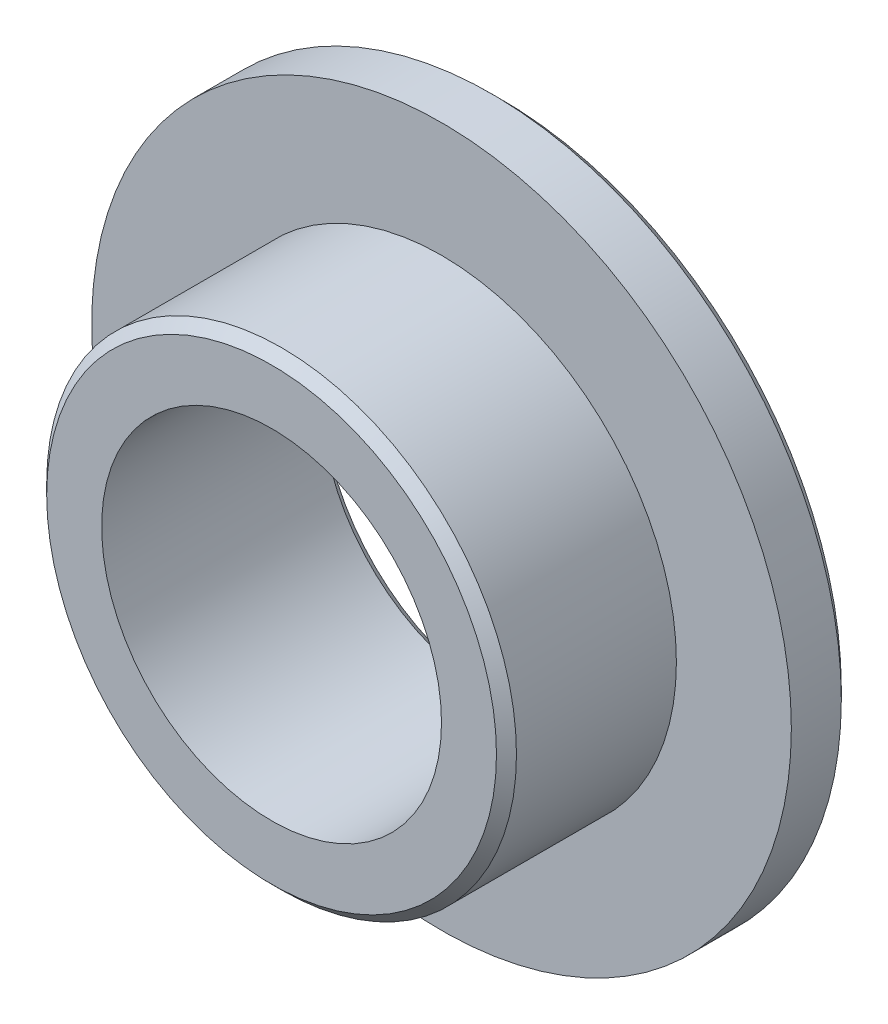
SolidWorks part; units mm, degrees
ref_plane "Piano frontale" through (0, 0, 0) normal (0, 0, 1) x (1, 0, 0)
ref_plane "Piano superiore" through (0, 0, 0) normal (0, 1, 0) x (1, 0, 0)
ref_plane "Piano destro" through (0, 0, 0) normal (1, 0, 0) x (0, 0, -1)
sketch "Schizzo1" plane through (0, 0, 0) normal (0, 0, 1) x (1, 0, 0)
  circle A0 centre (0, 0) radius 17.5
  dimension "D2" = 35
extrude "Estrusione1" add sketch "Schizzo1" along normal blind 3
sketch "Schizzo2" plane through (0, 0, 3) normal (0, 0, 1) x (1, 0, 0)
  circle A0 centre (0, 0) radius 11.75
  dimension "D1" = 23.5
extrude "Estrusione2" add sketch "Schizzo2" along normal blind 8.5
sketch "Schizzo3" plane through (0, 0, 11.5) normal (0, 0, 1) x (1, 0, 0)
  circle A0 centre (0, 0) radius 8.5
  dimension "D1" = 17
extrude "Estrusione3" cut sketch "Schizzo3" against normal through all
chamfer "Smusso1" distance 0.5 angle 45 3 edges at (11.75, 0, 11.5) (17.5, 0, 0) (8.5, 0, 0)
